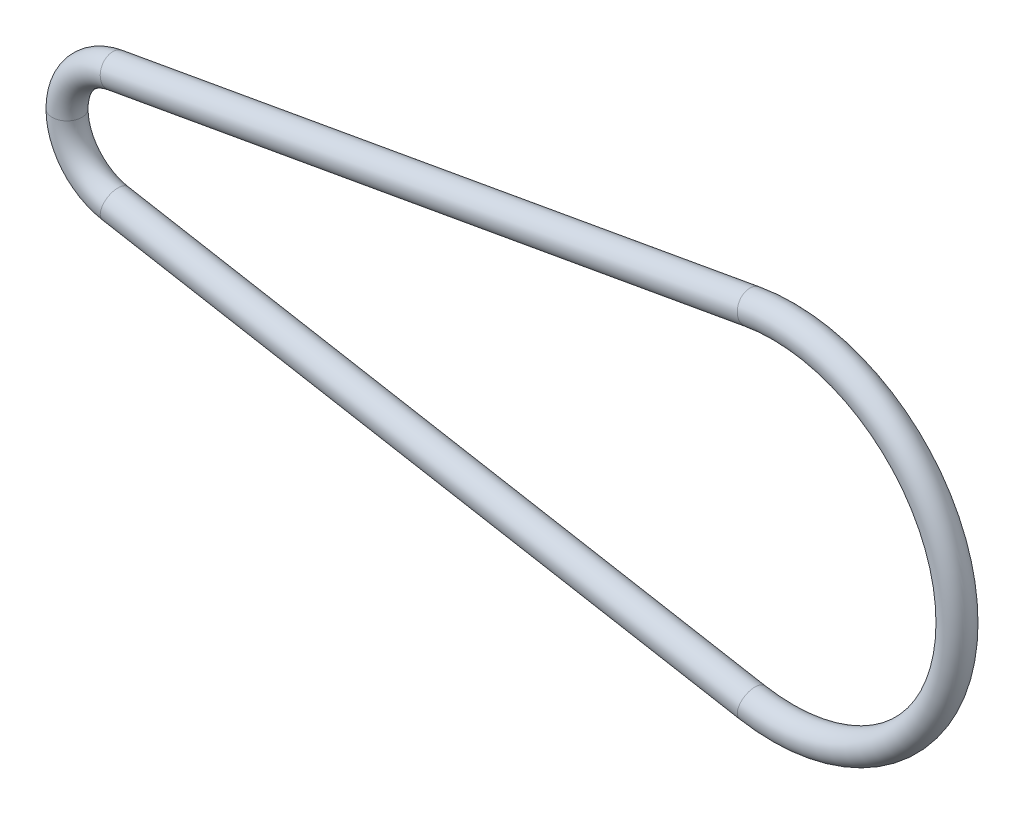
SolidWorks part; units mm, degrees
ref_plane "Front Plane" through (0, 0, 0) normal (0, 0, 1) x (1, 0, 0)
ref_plane "Top Plane" through (0, 0, 0) normal (0, 1, 0) x (1, 0, 0)
ref_plane "Right Plane" through (0, 0, 0) normal (1, 0, 0) x (0, 0, -1)
sketch "Sketch1" plane through (0, 0, 0) normal (0, 0, 1) x (1, 0, 0)
  line L0 (-0.9058, 5.076) -> (55.1449, 15.078)
  line L1 (-0.9058, -5.076) -> (55.1449, -15.078)
  arc A0 (-0.9058, -5.076) -> (-0.9058, 5.076) centre (0, 0) cw
  arc A1 (55.1449, 15.078) -> (55.1449, -15.078) centre (57.8355, 0) cw
  point P7 (0, 0)
  dimension "D1" = 5.1562
  dimension "D2" = 15.3162
  dimension "D3" = 181.7763
  dimension "D4" = 57.8355
sketch "Sketch2" plane through (0, 0, 0) normal (0, 1, 0) x (1, 0, 0)
  line L0 (-5.1562, 0) -> (-0.9058, 0) construction
  line L1 (-5.1562, 0) -> (-0.9058, 0) construction
  circle A0 centre (-5.1562, 0) radius 1.3081
  dimension "D1" = 2.6162
sweep "Sweep1" add profiles "Sketch2" path "Sketch1"
